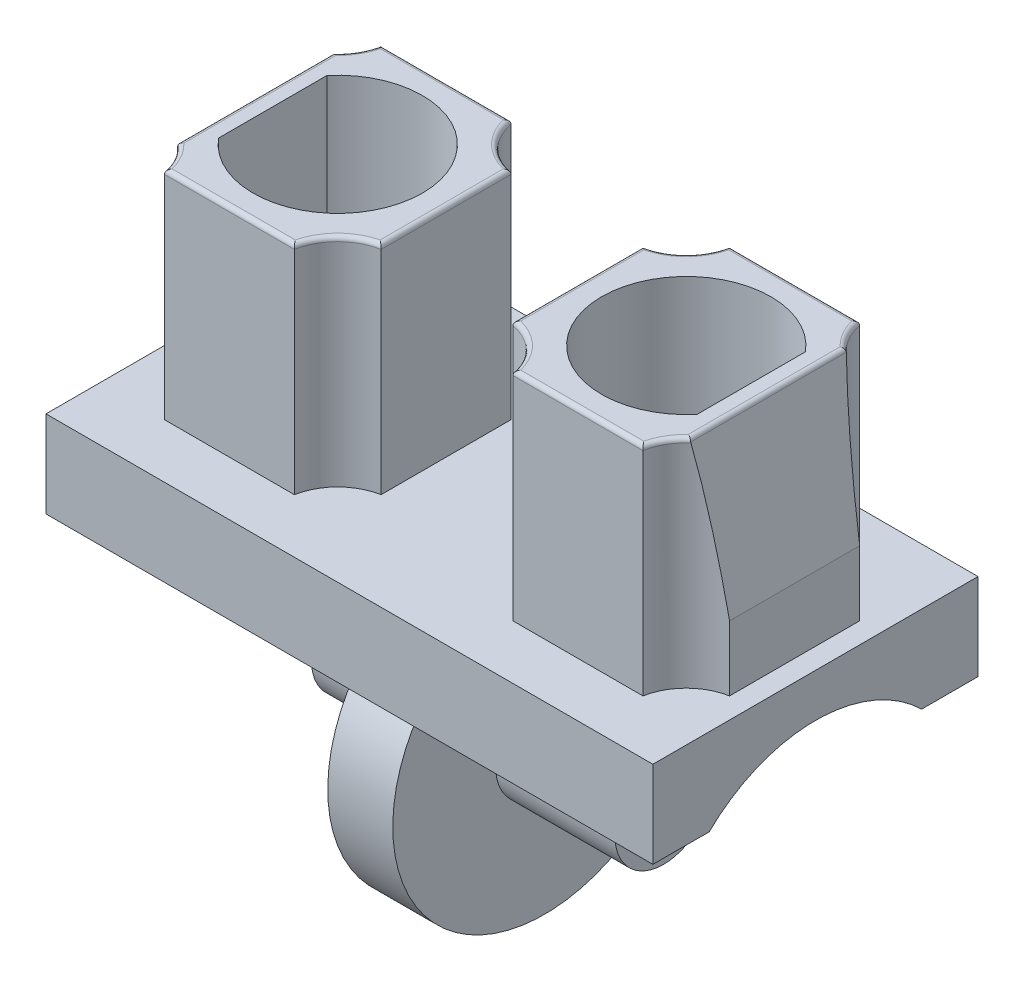
SolidWorks part; units mm, degrees
ref_plane "Front Plane" through (0, 0, 0) normal (0, 0, 1) x (1, 0, 0)
ref_plane "Top Plane" through (0, 0, 0) normal (0, 1, 0) x (1, 0, 0)
ref_plane "Right Plane" through (0, 0, 0) normal (1, 0, 0) x (0, 0, -1)
sketch "Sketch1" plane through (0, 0, 0) normal (1, 0, 0) x (0, 0, -1)
  circle A0 centre (0, 0) radius 3.5
  dimension "D1" = 7
extrude "Boss-Extrude1" add sketch "Sketch1" along normal blind 14
sketch "Sketch2" plane through (0, 0, 0) normal (1, 0, 0) x (0, 0, -1)
  line L0 (0, -7.3233) -> (0, 8.4987) construction
  line L1 (3.75, 4.5) -> (-3.75, 4.5)
  line L2 (-3.75, 4.5) -> (-3.75, 2.5)
  line L3 (-3.75, 2.5) -> (3.75, 2.5)
  line L4 (3.75, 4.5) -> (3.75, 2.5)
  circle A1 centre (0, 0) radius 3.5 construction
  point P10 (0, 2.5)
  point P11 (0, 4.5)
  dimension "D1" = 2
  dimension "D2" = 2.5
  dimension "D3" = 3.75
extrude "Boss-Extrude2" add sketch "Sketch2" along normal blind 14
sketch "Sketch4" plane through (14, 0, 0) normal (1, 0, 0) x (0, 0, -1)
  circle A0 centre (0, 0) radius 3.5
  circle A1 centre (0, 0) radius 1.125
  dimension "D1" = 7
  dimension "D2" = 2.25
extrude "Cut-Extrude1" cut sketch "Sketch4" against normal blind 6.25
sketch "Sketch5" plane through (0, 0, 0) normal (-1, 0, 0) x (0, 0, 1)
  circle A0 centre (0, 0) radius 3.5
  circle A1 centre (0, 0) radius 1.125
  dimension "D1" = 2.25
  dimension "D2" = 7
extrude "Cut-Extrude2" cut sketch "Sketch5" against normal blind 6.25
sketch "Sketch6" plane through (0, 0, 3.75) normal (0, 0, 1) x (1, 0, 0)
  line L0 (7, -5.1307) -> (7, 5.7302) construction
  line L1 (0, 1.125) -> (0, -1.125) construction
  line L2 (0, -1.495) -> (0, 1.7093)
  line L4 (4.5, 1.7093) -> (4.5, 0.875)
  line L5 (4.5, 0.875) -> (3.5, 0.875)
  line L6 (3.5, 0.875) -> (3.5, -1.495)
  line L7 (3.5, -1.495) -> (0, -1.495)
  line L8 (0, 1.7093) -> (4.5, 1.7093)
  line L10 (0, -1.125) -> (6.25, -1.125) construction
  line L11 (10.5, 0.875) -> (10.5, -1.495)
  line L12 (9.5, 1.7093) -> (9.5, 0.875)
  line L13 (9.5, 0.875) -> (10.5, 0.875)
  line L14 (10.5, -1.495) -> (14, -1.495)
  line L15 (14, -1.495) -> (14, 1.7093)
  line L16 (14, 1.7093) -> (9.5, 1.7093)
  dimension "D1" = 7
  dimension "D2" = 3.5
  dimension "D3" = 2
  dimension "D4" = 1
  dimension "D5" = 3.2043
  dimension "D6" = 2.37
extrude "Cut-Extrude3" cut sketch "Sketch6" against normal through all
sketch "Sketch7" plane through (0, 4.5, 0) normal (0, 1, 0) x (1, 0, 0)
  line L1 (0.48, 2.5) -> (5.48, 2.5)
  line L2 (5.48, 2.5) -> (5.48, -2.5)
  line L3 (5.48, -2.5) -> (0.48, -2.5)
  line L4 (0.48, -2.5) -> (0.48, 2.5)
  line L5 (7, -5.1531) -> (7, 4.7988) construction
  line L6 (0, 3.75) -> (0, -3.75) construction
  line L7 (8.52, -2.5) -> (13.52, -2.5)
  line L8 (8.52, 2.5) -> (8.52, -2.5)
  line L9 (13.52, 2.5) -> (8.52, 2.5)
  line L10 (13.52, -2.5) -> (13.52, 2.5)
  dimension "D1" = 7
  dimension "D2" = 5
  dimension "D3" = 5
  dimension "D4" = 0.48
  dimension "D5" = 2.5
extrude "Boss-Extrude3" add sketch "Sketch7" along normal blind 5
sketch "Sketch8" plane through (0, 0, 3.75) normal (0, 0, 1) x (1, 0, 0)
  line L0 (7, -4.6782) -> (7, 14.7825) construction
  line L1 (0, 4.5) -> (0, 2.5) construction
  line L6 (2.1578, 15.5151) -> (0.48, 15.5151)
  line L13 (0.48, 6) -> (2.1578, 15.5151)
  line L14 (0.48, 15.5151) -> (0.48, 6)
  line L15 (14, 4.5) -> (0, 4.5) construction
  line L17 (13.52, 6) -> (11.8422, 15.5151)
  line L18 (13.52, 15.5151) -> (13.52, 6)
  line L19 (11.8422, 15.5151) -> (13.52, 15.5151)
  dimension "D1" = 7
  dimension "D2" = 1.5
  dimension "D3" = 0.48
  dimension "D4" = 10
  dimension "D5" = 1.6778
extrude "Cut-Extrude4" cut sketch "Sketch8" against normal through all
sketch "Sketch9" plane through (0, 9.5, 0) normal (0, 1, 0) x (1, 0, 0)
  line L0 (5.48, 2.5) -> (0.48, 2.5) construction
  line L1 (5.48, -2.5) -> (5.48, 2.5) construction
  line L2 (4.48, 2.5) -> (5.48, 2.5)
  line L3 (5.48, 2.5) -> (5.48, 1.5)
  line L4 (2.98, 3.3673) -> (2.98, -4.3707) construction
  line L5 (0.48, 2.5) -> (0.48, -2.5) construction
  line L6 (0.48, 2.5) -> (0.48, 1.5)
  line L7 (0, 0) -> (7.4384, 0) construction
  line L8 (1.48, 2.5) -> (0.48, 2.5)
  line L9 (5.48, -2.5) -> (5.48, -1.5)
  line L10 (4.48, -2.5) -> (5.48, -2.5)
  line L11 (0.48, -2.5) -> (0.48, -1.5)
  line L12 (1.48, -2.5) -> (0.48, -2.5)
  line L16 (7, 4.3792) -> (7, -6.1156) construction
  line L17 (0, 3.75) -> (0, -3.75) construction
  line L18 (8.52, -2.5) -> (8.52, -1.5)
  line L19 (9.52, -2.5) -> (8.52, -2.5)
  line L20 (12.52, -2.5) -> (13.52, -2.5)
  line L21 (13.52, -2.5) -> (13.52, -1.5)
  line L22 (13.52, 2.5) -> (13.52, 1.5)
  line L23 (12.52, 2.5) -> (13.52, 2.5)
  line L24 (8.52, 2.5) -> (8.52, 1.5)
  line L25 (9.52, 2.5) -> (8.52, 2.5)
  arc A1 (4.48, 2.5) -> (5.48, 1.5) centre (5.7089, 2.7289) ccw
  arc A2 (1.48, 2.5) -> (0.48, 1.5) centre (0.2511, 2.7289) cw
  arc A3 (4.48, -2.5) -> (5.48, -1.5) centre (5.7089, -2.7289) cw
  arc A4 (1.48, -2.5) -> (0.48, -1.5) centre (0.2511, -2.7289) ccw
  arc A5 (9.52, -2.5) -> (8.52, -1.5) centre (8.2911, -2.7289) ccw
  arc A6 (12.52, -2.5) -> (13.52, -1.5) centre (13.7489, -2.7289) cw
  arc A7 (12.52, 2.5) -> (13.52, 1.5) centre (13.7489, 2.7289) ccw
  arc A8 (9.52, 2.5) -> (8.52, 1.5) centre (8.2911, 2.7289) cw
  dimension "D1" = 1.25
  dimension "D2" = 1
  dimension "D3" = 1
  dimension "D4" = 2.5
  dimension "D5" = 7
extrude "Cut-Extrude5" cut sketch "Sketch9" against normal blind 5
fillet "Fillet1" radius 0.1 16 edges at (1.0971, 9.5, 0) (2.98, 9.5, -2.5) (4.825, 9.5, -1.845) (5.48, 9.5, 0) (4.825, 9.5, 1.845) (2.98, 9.5, 2.5) (8.52, 9.5, 0) (9.175, 9.5, -1.845) (11.02, 9.5, -2.5) (12.9029, 9.5, 0) (11.02, 9.5, 2.5) (9.175, 9.5, 1.845) (1.3446, 9.5, -2.1233) (1.3446, 9.5, 2.1233) (12.6554, 9.5, -2.1233) (12.6554, 9.5, 2.1233)
sketch "Sketch10" plane through (0, 9.5, 0) normal (0, 1, 0) x (1, 0, 0)
  line L0 (7, -4.768) -> (7, 5.2456) construction
  line L1 (0, 3.75) -> (0, -3.75) construction
  line L2 (1.48, 1.25) -> (1.48, -1.25)
  line L3 (4.48, 2.5) -> (1.48, 2.5) construction
  line L4 (0.48, 1.5) -> (0.48, -1.5) construction
  line L5 (5.48, -1.5) -> (5.48, 1.5) construction
  line L6 (12.52, 1.25) -> (12.52, -1.25)
  arc A0 (1.48, 1.25) -> (1.48, -1.25) centre (2.98, 0) cw
  arc A1 (12.52, 1.25) -> (12.52, -1.25) centre (11.02, 0) ccw
  dimension "D1" = 7
  dimension "D2" = 2.5
  dimension "D3" = 2.5
  dimension "D4" = 1
  dimension "D5" = 2.5
extrude "Cut-Extrude6" cut sketch "Sketch10" against normal blind 5
